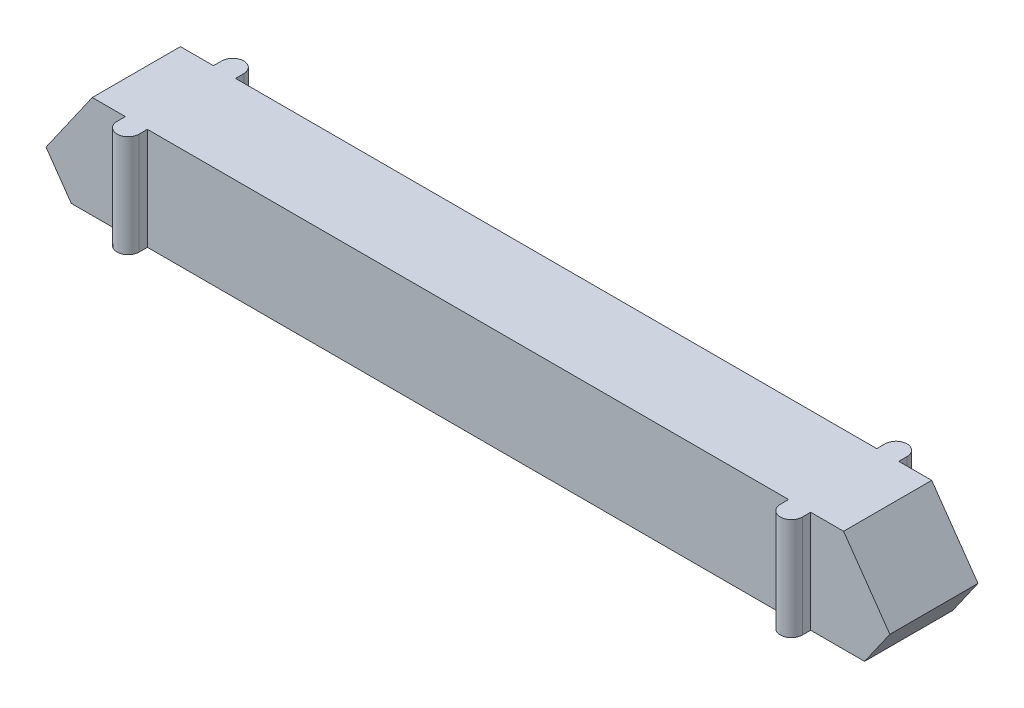
SolidWorks part; units mm, degrees
ref_plane "Front Plane" through (0, 0, 0) normal (0, 0, 1) x (1, 0, 0)
ref_plane "Top Plane" through (0, 0, 0) normal (0, 1, 0) x (1, 0, 0)
ref_plane "Right Plane" through (0, 0, 0) normal (1, 0, 0) x (0, 0, -1)
sketch "Sketch3" plane through (0, 0, 0) normal (0, 0, 1) x (1, 0, 0)
  line L0 (0, 0) -> (14.5688, -20.8065)
  line L1 (14.5688, -20.8065) -> (471.7688, -20.8065)
  line L2 (471.7688, -20.8065) -> (486.3377, 0)
  line L3 (486.3377, 0) -> (459.6598, 38.1)
  line L4 (459.6598, 38.1) -> (26.6779, 38.1)
  line L5 (26.6779, 38.1) -> (0, 0)
  dimension "D1" = 457.2
  dimension "D2" = 25.4
  dimension "D3" = 38.1
  dimension "D4" = 125
  dimension "D5" = 125
  dimension "D6" = 125
  dimension "1.5" = 38.1
  dimension "D7" = 125
extrude "Boss-Extrude3" add sketch "Sketch3" along normal blind 50.8
sketch "Sketch4" plane through (0, 38.1, 0) normal (0, 1, 0) x (1, 0, 0)
  line L2 (459.6598, -50.8) -> (26.6779, -50.8) construction
  line L3 (26.6779, -50.8) -> (26.6779, 0) construction
  line L4 (45.7279, -55.5625) -> (45.7279, -50.8)
  line L5 (58.4279, -55.5625) -> (58.4279, -50.8)
  line L6 (45.7279, -50.8) -> (58.4279, -50.8)
  arc A0 (45.7279, -55.5625) -> (58.4279, -55.5625) centre (52.0779, -55.5625) ccw
  dimension "D1" = 12.7
  dimension "D2" = 4.7625
  dimension "D3" = 25.4
extrude "Boss-Extrude4" add sketch "Sketch4" against normal up to surface (58.9065 mm away) up to face at (243.1688, -20.8065, 25.4)
ref_plane "Plane1" through (243.205, 0, 0) normal (1, 0, 0) x (0, 0, -1)
ref_plane "Plane2" through (0, 0, 25.4) normal (0, 0, 1) x (1, 0, 0)
mirror "Mirror1" about plane through (243.205, 0, 0) normal (1, 0, 0) of "Boss-Extrude4" second plane through (0, 0, 25.4) second plane normal (0, 0, 1)
